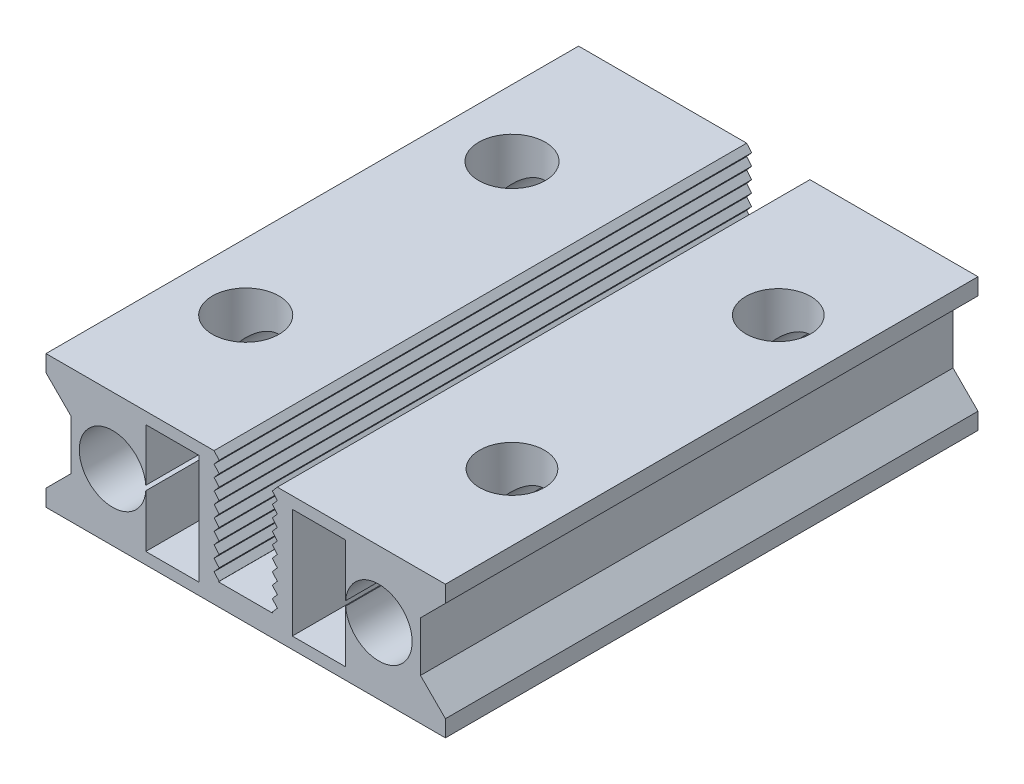
SolidWorks part; units mm, degrees
ref_plane "前视基准面" through (0, 0, 0) normal (0, 0, 1) x (1, 0, 0)
ref_plane "上视基准面" through (0, 0, 0) normal (0, 1, 0) x (1, 0, 0)
ref_plane "右视基准面" through (0, 0, 0) normal (1, 0, 0) x (0, 0, -1)
sketch "草图1" plane through (0, 0, 0) normal (0, 0, 1) x (1, 0, 0)
  line L0 (-12, 8) -> (-12, 7)
  line L1 (-12, 7) -> (-10.5, 5.5)
  line L2 (-10.5, 5.5) -> (-10.5, 2.5)
  line L3 (-10.5, 2.5) -> (-12, 1)
  line L4 (-12, 1) -> (-12, 0)
  line L5 (-12, 0) -> (12, 0)
  line L6 (12, 0) -> (12, 1)
  line L7 (12, 1) -> (10.5, 2.5)
  line L8 (10.5, 2.5) -> (10.5, 5.5)
  line L9 (10.5, 5.5) -> (12, 7)
  line L10 (12, 7) -> (12, 8)
  line L11 (12, 8) -> (1.9, 8)
  line L12 (0, 0) -> (0, 8) construction
  line L13 (-8, 4) -> (8, 4) construction
  line L14 (-1.9, 8) -> (-1.9, 1.3)
  line L15 (-6.005, 7.3) -> (-2.8, 7.3)
  line L16 (-6.005, 7.3) -> (-6.005, 4.1413)
  line L17 (-6.005, 0.7) -> (-2.8, 0.7)
  line L18 (-2.8, 7.3) -> (-2.8, 0.7)
  line L19 (-1.9, 1.3) -> (1.9, 1.3)
  line L20 (1.9, 1.3) -> (1.9, 8)
  line L21 (-1.9, 8) -> (-12, 8)
  line L22 (-6.005, 3.8587) -> (-6.005, 0.7)
  line L23 (2.8, 7.3) -> (6.005, 7.3)
  line L24 (2.8, 7.3) -> (2.8, 0.7)
  line L25 (2.8, 0.7) -> (6.005, 0.7)
  line L26 (6.005, 7.3) -> (6.005, 4.1413)
  line L27 (6.005, 3.8587) -> (6.005, 0.7)
  arc A0 (-6.005, 4.1413) -> (-6, 4) centre (-8, 4) ccw
  arc A1 (6.005, 3.8587) -> (6.005, 4.1413) centre (8, 4) ccw
  point P19 (10.5, 4)
  point P24 (-2.8, 4)
  point P27 (0, 1.3)
  dimension "D4" = 4
  dimension "D1" = 24
  dimension "D2" = 8
  dimension "D3" = 45
  dimension "D5" = 16
  dimension "D6" = 8
  dimension "D7" = 3
  dimension "D8" = 1
  dimension "D9" = 4
  dimension "D10" = 3.8
  dimension "D11" = 1.3
  dimension "D12" = 5.6
  dimension "D13" = 2.8
  dimension "D14" = 12.01
  dimension "D15" = 0.7
extrude "凸台-拉伸2" add sketch "草图1" along normal blind 32 contours L14 L21 L0 L1 L2 L3 L4 L5 L6 L7 L8 L9 L10 L11 L20 L19 A1 L27 L25 L24 L23 L26 A0 L16 L15 L18 L17 L22
sketch "草图3" plane through (0, 0, 32) normal (0, 0, 1) x (1, 0, 0)
  line L0 (-1.9, 8) -> (-1.6, 7.65)
  line L1 (-1.6, 7.65) -> (-1.9, 7.3)
  line L2 (-1.9, 8) -> (-1.9, 1.3) construction
  line L3 (-1.9, 7.3) -> (-1.9, 8)
  point P7 (-1.9, 7.65)
  dimension "D1" = 0.7
  dimension "D2" = 0.3
extrude "凸台-拉伸3" add sketch "草图3" against normal up to surface (32 mm away) up to face at (5.6025, 4, 0)
pattern_linear "阵列(线性)1" count 10 spacing 0.7 along (0, -1, 0) of "凸台-拉伸3"
mirror "镜向1" about plane through (0, 0, 0) normal (1, 0, 0) of "阵列(线性)1", "凸台-拉伸3"
sketch "草图4" plane through (0, 8, 0) normal (0, 1, 0) x (1, 0, 0)
  line L1 (12, 0) -> (1.9, 0) construction
  circle A0 centre (-8, -8) radius 2
  circle A1 centre (8, -8) radius 1.95
  dimension "D1" = 16
  dimension "D4" = 3.9
  dimension "D5" = 4
  dimension "D2" = 8
  dimension "D3" = 8
extrude "切除-拉伸1" cut sketch "草图4" against normal through all
pattern_linear "阵列(线性)2" count 2 spacing 16 along (0, 0, 1) of "切除-拉伸1"
equation "\"D13@草图1\"=\"D12@草图1\"/2"
